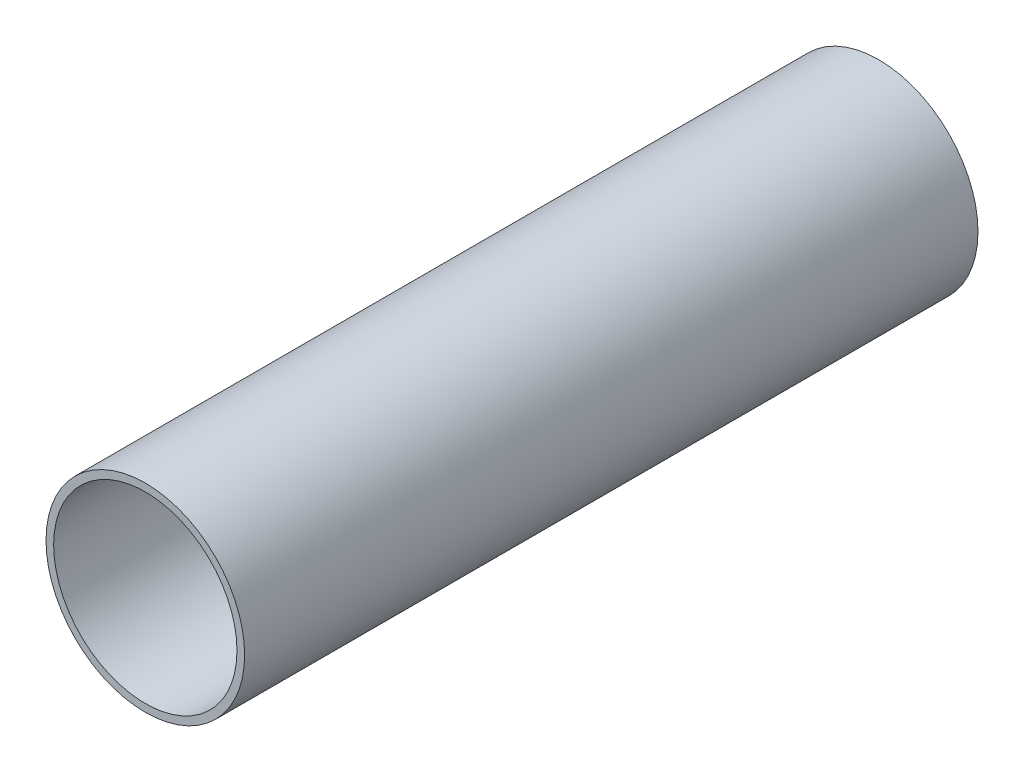
SolidWorks part; units mm, degrees
material "Acrylic (Medium-high impact)"
ref_plane "Front Plane" through (0, 0, 0) normal (0, 0, 1) x (1, 0, 0)
ref_plane "Top Plane" through (0, 0, 0) normal (0, 1, 0) x (1, 0, 0)
ref_plane "Right Plane" through (0, 0, 0) normal (1, 0, 0) x (0, 0, -1)
sketch "Sketch1" plane through (0, 0, 0) normal (0, 0, 1) x (1, 0, 0)
  circle A0 centre (0, 0) radius 82.55
  circle A1 centre (0, 0) radius 76.2
  dimension "D1" = 165.1
  dimension "D2" = 152.4
extrude "Boss-Extrude1" add sketch "Sketch1" along normal blind 609.6
